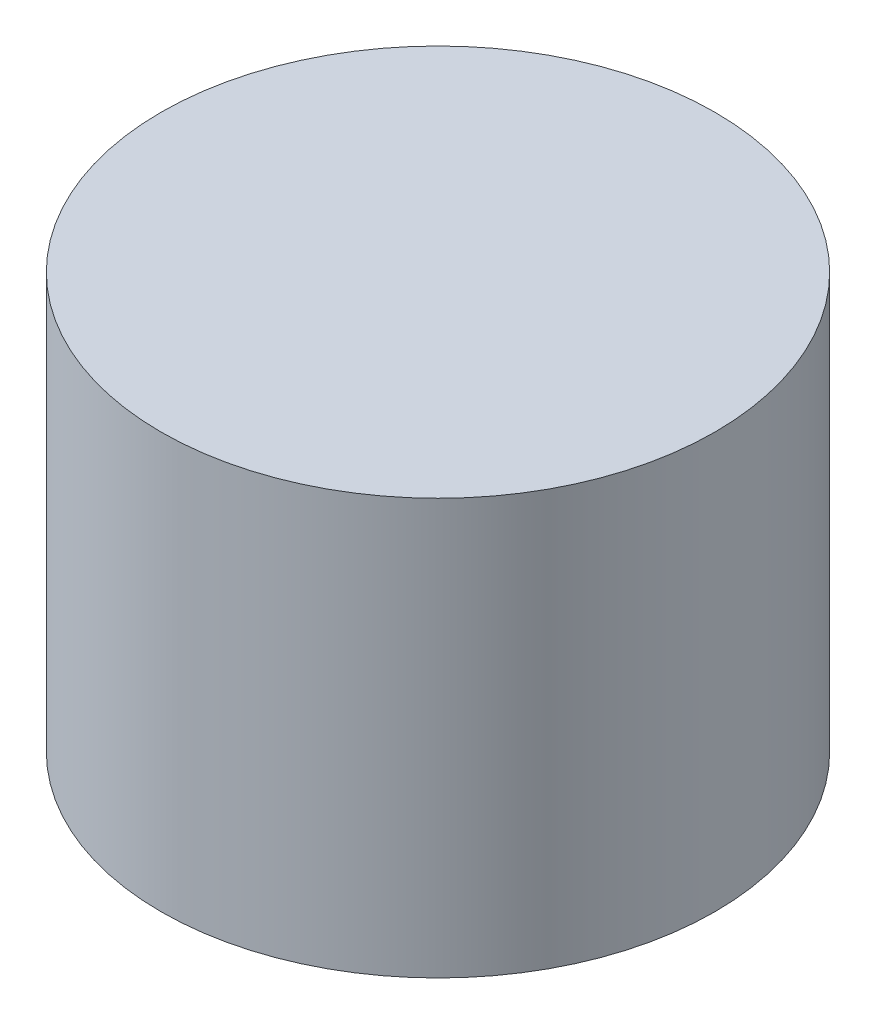
SolidWorks part; units mm, degrees
ref_plane "Front Plane" through (0, 0, 0) normal (0, 0, 1) x (1, 0, 0)
ref_plane "Top Plane" through (0, 0, 0) normal (0, 1, 0) x (1, 0, 0)
ref_plane "Right Plane" through (0, 0, 0) normal (1, 0, 0) x (0, 0, -1)
sketch "Sketch1" plane through (0, 0, 0) normal (0, 1, 0) x (1, 0, 0)
  circle A0 centre (-36.4453, 29.867) radius 8
  dimension "D1" = 16
extrude "Boss-Extrude1" add sketch "Sketch1" along normal blind 12
